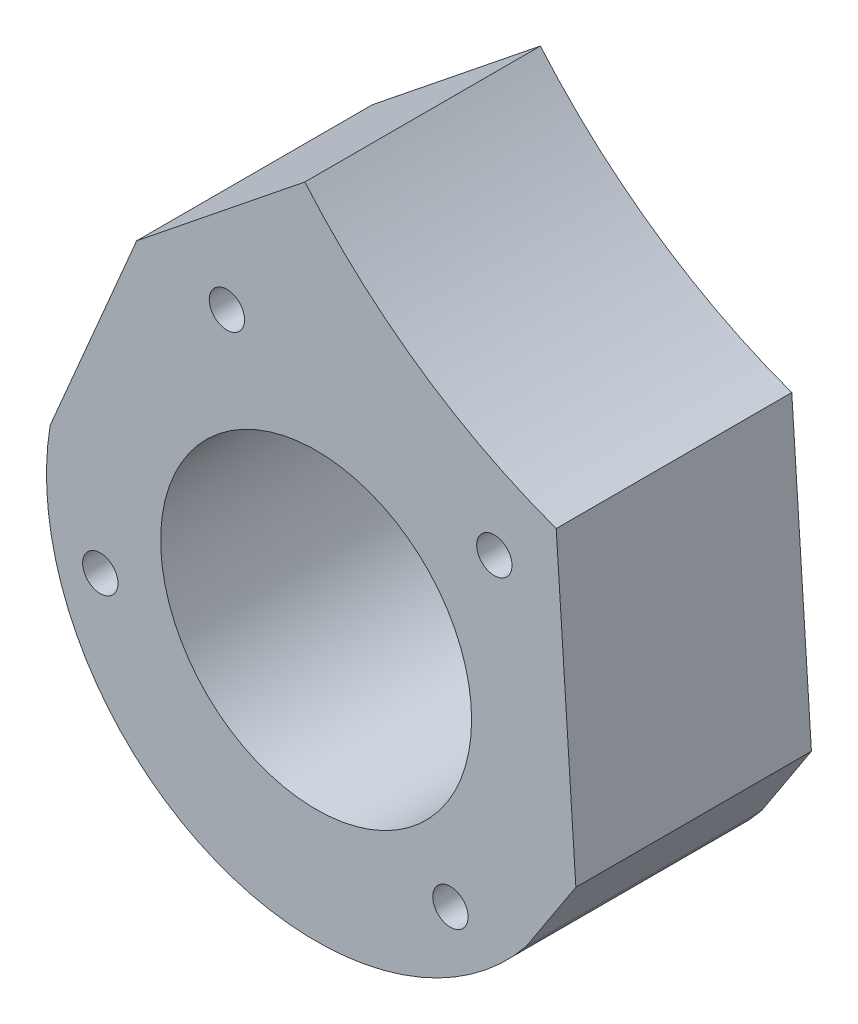
SolidWorks part; units mm, degrees
ref_plane "前视基准面" through (0, 0, 0) normal (0, 0, 1) x (1, 0, 0)
ref_plane "上视基准面" through (0, 0, 0) normal (0, 1, 0) x (1, 0, 0)
ref_plane "右视基准面" through (0, 0, 0) normal (1, 0, 0) x (0, 0, -1)
sketch "草图1" plane through (0, 0, 0) normal (0, 0, 1) x (1, 0, 0)
  line L0 (-26.6367, 37.9915) -> (-33.982, 20.7547)
  line L9 (-26.6367, 37.9915) -> (-12.8825, 49.0329)
  line L13 (10.652, 9.1032) -> (6.4448, 2.6615)
  line L14 (10.652, 9.1032) -> (8.9821, 34.6443)
  line L15 (-12.8825, 49.0329) -> (-12.3604, 49.4521)
  arc A1 (-33.982, 20.7547) -> (6.4448, 2.6615) centre (-11.401, 16.9983) ccw
  circle A3 centre (-11.401, 16.9983) radius 13.2
  arc A4 (-12.3604, 49.4521) -> (8.9821, 34.6443) centre (26.4246, 82.5688) ccw
extrude "凸台-拉伸1" add sketch "草图1" along normal blind 20
sketch "Sketch1" plane through (0, 0, 0) normal (0, 0, -1) x (-1, 0, 0)
  circle A0 centre (-3.7299, 30.0545) radius 1.5
  circle A1 centre (-311.4033, -148.7025) radius 1.5
  circle A2 centre (18.9759, 36.7569) radius 1.5
  circle A3 centre (29.7234, 12.0051) radius 1.5
  circle A4 centre (0, 2.3393) radius 1.5
  point P4 (-3.5374, 31.3177)
  point P7 (14.7619, 39.1686)
  point P10 (29.7234, 12.0051)
  point P13 (0, 2.3393)
  point P14 (18.9759, 36.7569)
  point P15 (-3.7299, 30.0545)
extrude "Cut-Extrude1" cut sketch "Sketch1" against normal through all
